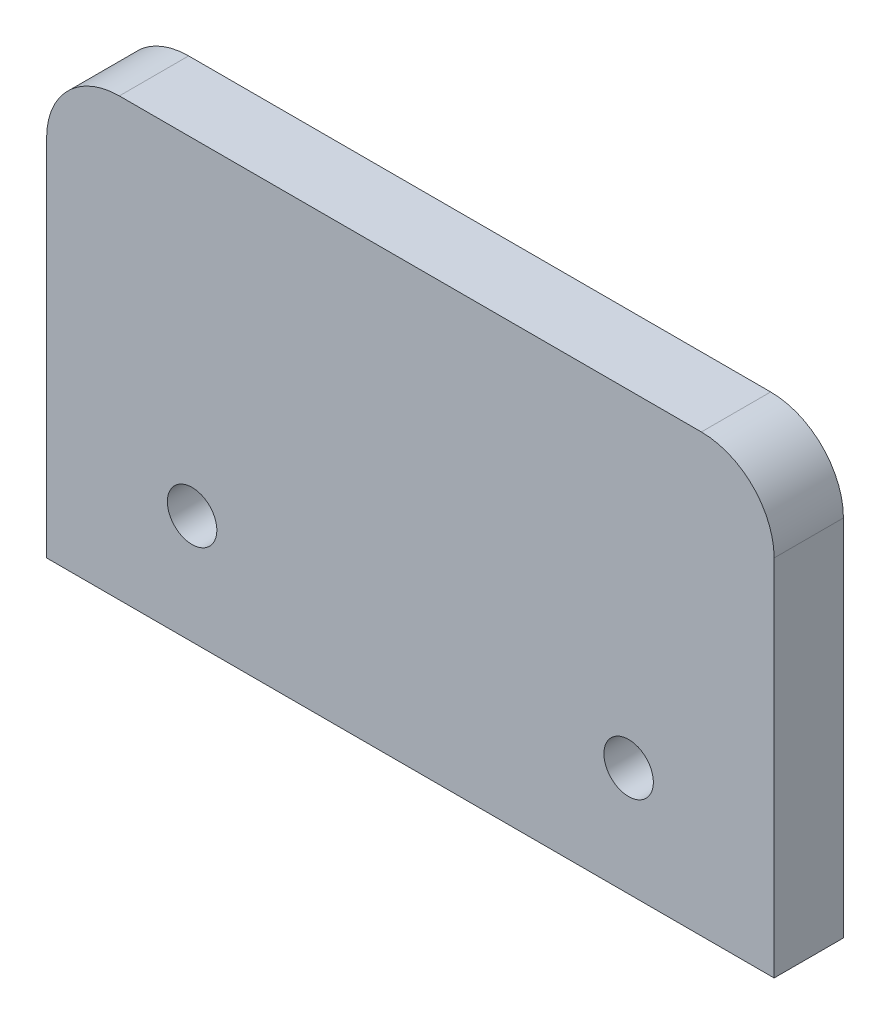
SolidWorks part; units mm, degrees
ref_plane "Plano frontal" through (0, 0, 0) normal (0, 0, 1) x (1, 0, 0)
ref_plane "Plano superior" through (0, 0, 0) normal (0, 1, 0) x (1, 0, 0)
ref_plane "Plano direito" through (0, 0, 0) normal (1, 0, 0) x (0, 0, -1)
sketch "Esboço1" plane through (0, 0, 0) normal (0, 0, 1) x (1, 0, 0)
  line L1 (50, -30) -> (-50, -30)
  line L2 (50, -30) -> (50, 30)
  line L3 (50, 30) -> (-50, 30)
  line L4 (-50, -30) -> (-50, 30)
  line L5 (50, -30) -> (-50, 30) construction
  line L6 (50, 30) -> (-50, -30) construction
  point P0 (0, 0)
  dimension "D1" = 100
  dimension "D2" = 60
extrude "Ressalto-extrusão1" add sketch "Esboço1" along normal blind 9.525
fillet "Filete1" radius 10 2 edges at (-50, 30, 4.7625) (50, 30, 4.7625)
sketch "Esboço2" plane through (0, -30, 0) normal (0, -1, 0) x (1, 0, 0)
  line L0 (-50, 4.7625) -> (50, 4.7625) construction
  line L1 (-50, 9.525) -> (-50, 0) construction
  line L2 (50, 9.525) -> (50, 0) construction
  circle A0 centre (-20, 4.7625) radius 3
  circle A1 centre (20, 4.7625) radius 3
  dimension "D3" = 6
  dimension "D1" = 30
  dimension "D2" = 30
hole_wizard "Furo roscado de M61" positions "Esboço3" profile "Esboço4" tap size "M6" standard "ISO"
sketch "Esboço3" plane through (0, -30, 0) normal (0, -1, 0) x (-1, 0, 0)
  point P0 (20, -4.7625)
  point P3 (-20, -4.7625)
cosmetic thread "Rosca de furo1"
cosmetic thread "Rosca de furo2"
sketch "Esboço4" plane through (-20, -30, 4.7625) normal (1, 0, 0) x (0, 0, -1)
  line L0 (0, 0) -> (0, 16.5022)
  line L1 (0, 16.5022) -> (2.5, 15)
  line L2 (2.5, 15) -> (2.5, 0)
  line L5 (2.5, 0) -> (0, 0)
  line L10 (0, 16.5022) -> (-2.5, 15) construction
  line L11 (0, -6.35) -> (0, 107.95) construction
  dimension "Tap Drill Dia." = 5
  dimension "Tap Drill Depth" = 15
  dimension "Drill Angle" = 118
sketch "Esboço5" plane through (0, 0, 9.525) normal (0, 0, 1) x (1, 0, 0)
  line L0 (-50, 20) -> (-50, -30) construction
  line L1 (-50, -30) -> (50, -30) construction
  line L2 (50, -30) -> (50, 20) construction
  circle A0 centre (30, -15) radius 3
  circle A1 centre (-30, -15) radius 3
  point P12 (31.7818, -30)
  dimension "D1" = 6
  dimension "D2" = 20
  dimension "D3" = 15
  dimension "D4" = 20
  dimension "D5" = 15
extrude "Corte-extrusão1" cut sketch "Esboço5" against normal through all
hole_wizard "Furo roscado de M82" positions "3DSketch1" profile "Esboço8" tap size "M8" standard "ISO" end condition through all
sketch3d "3DSketch1"
  line L0 (30, -15, 0) -> (30, -15, 9.525) construction
  line L1 (-30, -15, 0) -> (-30, -15, 9.525) construction
  point P0 (30, -15, 0)
  point P4 (-30, -15, 0)
sketch "Esboço8" plane through (30, -15, 0) normal (1, 0, 0) x (0, 1, 0)
  line L0 (0, 0) -> (0, 9.525)
  line L1 (0, 9.525) -> (3.4, 9.525)
  line L2 (3.4, 9.525) -> (3.4, 0)
  line L5 (3.4, 0) -> (0, 0)
  line L11 (0, -6.35) -> (0, 107.95) construction
  dimension "Thru Tap Drill Dia." = 6.8
  dimension "Thru Tap Drill Depth" = 9.525
cosmetic thread "Rosca de furo3" parameters "D2"=8
cosmetic thread "Rosca de furo4" parameters "D2"=8
